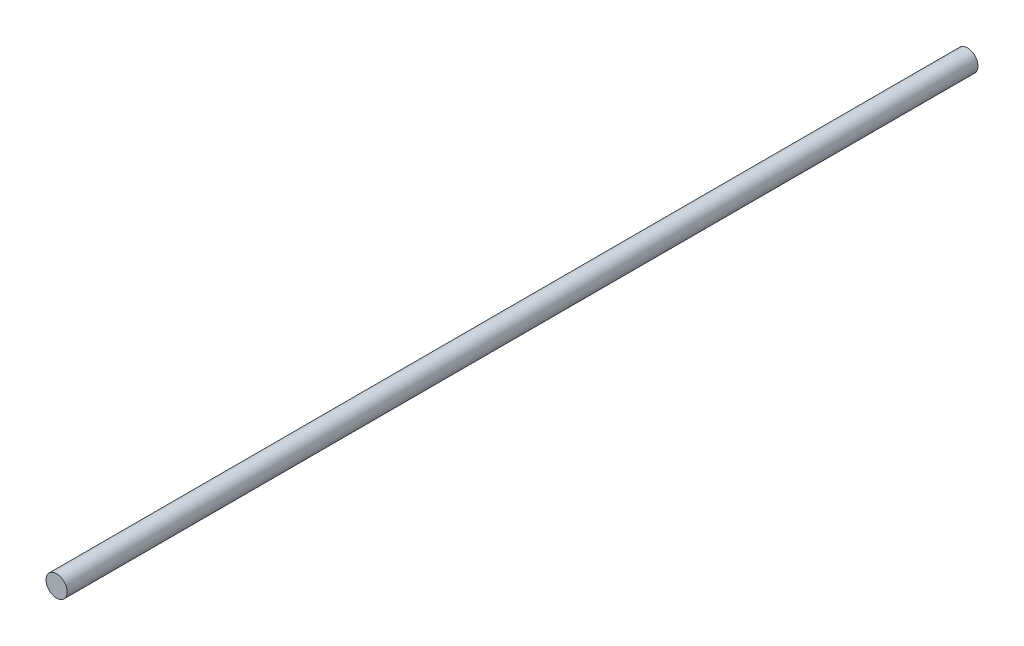
SolidWorks part; units mm, degrees
material "Plain Carbon Steel"
ref_plane "Front Plane" through (0, 0, 0) normal (0, 0, 1) x (1, 0, 0)
ref_plane "Top Plane" through (0, 0, 0) normal (0, 1, 0) x (1, 0, 0)
ref_plane "Right Plane" through (0, 0, 0) normal (1, 0, 0) x (0, 0, -1)
sketch "Sketch1" plane through (0, 0, 0) normal (0, 0, 1) x (1, 0, 0)
  circle A0 centre (0, 0) radius 2.5
  dimension "D1" = 5
extrude "Boss-Extrude1" add sketch "Sketch1" along normal blind 215
cosmetic thread "Cosmetic Thread1" parameters "D2"=4.11
